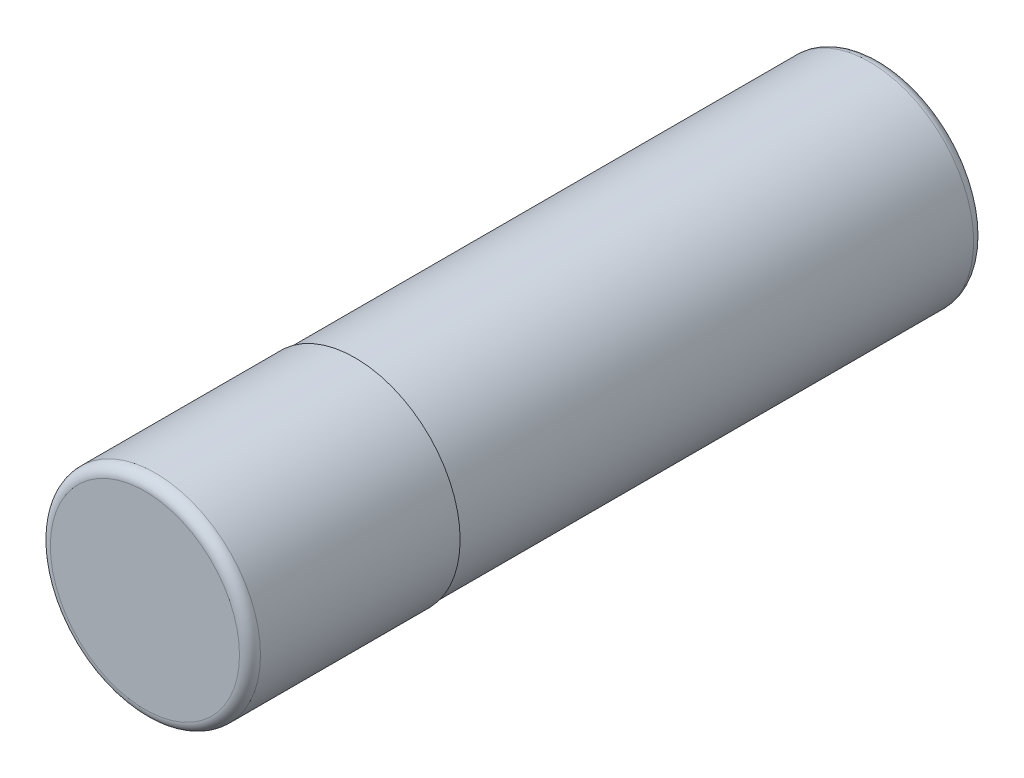
SolidWorks part; units mm, degrees
ref_plane "정면" through (0, 0, 0) normal (0, 0, 1) x (1, 0, 0)
ref_plane "윗면" through (0, 0, 0) normal (0, 1, 0) x (1, 0, 0)
ref_plane "우측면" through (0, 0, 0) normal (1, 0, 0) x (0, 0, -1)
sketch "스케치1" plane through (0, 0, 0) normal (0, 0, 1) x (1, 0, 0)
  circle A0 centre (0, 0) radius 1.975
  dimension "D1" = 3.95
extrude "보스-돌출1" add sketch "스케치1" along normal blind 10
fillet "필렛1" radius 0.2 1 edges at (1.975, 0, 0)
sketch "스케치2" plane through (0, 0, 10) normal (0, 0, 1) x (1, 0, 0)
  circle A0 centre (0, 0) radius 2
  dimension "D1" = 4
extrude "보스-돌출2" add sketch "스케치2" along normal blind 4
fillet "필렛2" radius 0.2 1 edges at (2, 0, 14)
